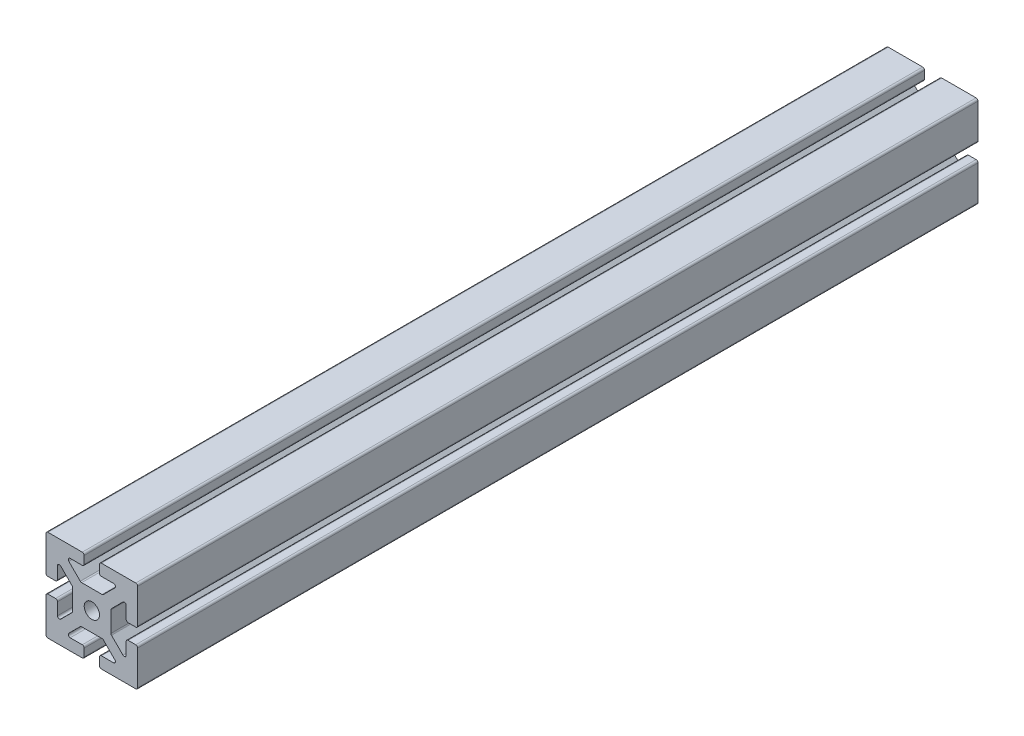
SolidWorks part; units mm, degrees
material "6061-T4 (SS)"
ref_plane "Front Plane" through (0, 0, 0) normal (0, 0, 1) x (1, 0, 0)
ref_plane "Top Plane" through (0, 0, 0) normal (0, 1, 0) x (1, 0, 0)
ref_plane "Right Plane" through (0, 0, 0) normal (1, 0, 0) x (0, 0, -1)
sketch "Sketch2" plane through (0, 0, 0) normal (0, 0, 1) x (1, 0, 0)
  line L0 (0, 0) -> (0, 2.5) construction
  line L1 (0, 0) -> (2.5, 0) construction
  line L2 (0, 2.5) -> (1.3358, 2.5)
  line L3 (1.5126, 2.5732) -> (3.0126, 4.0732)
  line L4 (2.8358, 4.5) -> (1.25, 4.5)
  line L5 (1, 4.75) -> (1, 5.75)
  line L6 (1.25, 6) -> (5.75, 6)
  line L7 (6, 5.75) -> (6, 1.25)
  line L8 (5.75, 1) -> (4.75, 1)
  line L9 (4.5, 1.25) -> (4.5, 2.8358)
  line L10 (4.0732, 3.0126) -> (2.5732, 1.5126)
  line L11 (2.5, 1.3358) -> (2.5, 0)
  line L12 (0, 0) -> (5.75, 5.75) construction
  line L13 (2.5, 0) -> (2.5, -1.3358)
  line L14 (2.5732, -1.5126) -> (4.0732, -3.0126)
  line L15 (4.5, -2.8358) -> (4.5, -1.25)
  line L16 (4.75, -1) -> (5.75, -1)
  line L17 (6, -1.25) -> (6, -5.75)
  line L18 (5.75, -6) -> (1.25, -6)
  line L19 (1, -5.75) -> (1, -4.75)
  line L20 (1.25, -4.5) -> (2.8358, -4.5)
  line L21 (3.0126, -4.0732) -> (1.5126, -2.5732)
  line L22 (1.3358, -2.5) -> (0, -2.5)
  line L23 (0, -2.5) -> (-1.3358, -2.5)
  line L24 (-1.5126, -2.5732) -> (-3.0126, -4.0732)
  line L25 (-2.8358, -4.5) -> (-1.25, -4.5)
  line L26 (-1, -4.75) -> (-1, -5.75)
  line L27 (-1.25, -6) -> (-5.75, -6)
  line L28 (-6, -5.75) -> (-6, -1.25)
  line L29 (-5.75, -1) -> (-4.75, -1)
  line L30 (-4.5, -1.25) -> (-4.5, -2.8358)
  line L31 (-4.0732, -3.0126) -> (-2.5732, -1.5126)
  line L32 (-2.5, -1.3358) -> (-2.5, 0)
  line L33 (-2.5, 0) -> (-2.5, 1.3358)
  line L34 (-2.5732, 1.5126) -> (-4.0732, 3.0126)
  line L35 (-4.5, 2.8358) -> (-4.5, 1.25)
  line L36 (-4.75, 1) -> (-5.75, 1)
  line L37 (-6, 1.25) -> (-6, 5.75)
  line L38 (-5.75, 6) -> (-1.25, 6)
  line L39 (-1, 5.75) -> (-1, 4.75)
  line L40 (-1.25, 4.5) -> (-2.8358, 4.5)
  line L41 (-3.0126, 4.0732) -> (-1.5126, 2.5732)
  line L42 (-1.3358, 2.5) -> (0, 2.5)
  circle A0 centre (0, 0) radius 1
  arc A1 (2.5732, 1.5126) -> (2.5, 1.3358) centre (2.75, 1.3358) ccw
  arc A2 (4.5, 2.8358) -> (4.0732, 3.0126) centre (4.25, 2.8358) ccw
  arc A3 (4.75, 1) -> (4.5, 1.25) centre (4.75, 1.25) cw
  arc A4 (6, 1.25) -> (5.75, 1) centre (5.75, 1.25) cw
  arc A5 (5.75, 6) -> (6, 5.75) centre (5.75, 5.75) cw
  arc A6 (1, 5.75) -> (1.25, 6) centre (1.25, 5.75) cw
  arc A7 (1.25, 4.5) -> (1, 4.75) centre (1.25, 4.75) cw
  arc A8 (3.0126, 4.0732) -> (2.8358, 4.5) centre (2.8358, 4.25) ccw
  arc A9 (1.3358, 2.5) -> (1.5126, 2.5732) centre (1.3358, 2.75) ccw
  arc A10 (1.5126, -2.5732) -> (1.3358, -2.5) centre (1.3358, -2.75) ccw
  arc A11 (2.8358, -4.5) -> (3.0126, -4.0732) centre (2.8358, -4.25) ccw
  arc A12 (1, -4.75) -> (1.25, -4.5) centre (1.25, -4.75) cw
  arc A13 (1.25, -6) -> (1, -5.75) centre (1.25, -5.75) cw
  arc A14 (6, -5.75) -> (5.75, -6) centre (5.75, -5.75) cw
  arc A15 (5.75, -1) -> (6, -1.25) centre (5.75, -1.25) cw
  arc A16 (4.5, -1.25) -> (4.75, -1) centre (4.75, -1.25) cw
  arc A17 (4.0732, -3.0126) -> (4.5, -2.8358) centre (4.25, -2.8358) ccw
  arc A18 (2.5, -1.3358) -> (2.5732, -1.5126) centre (2.75, -1.3358) ccw
  arc A19 (-2.5732, -1.5126) -> (-2.5, -1.3358) centre (-2.75, -1.3358) ccw
  arc A20 (-4.5, -2.8358) -> (-4.0732, -3.0126) centre (-4.25, -2.8358) ccw
  arc A21 (-4.75, -1) -> (-4.5, -1.25) centre (-4.75, -1.25) cw
  arc A22 (-6, -1.25) -> (-5.75, -1) centre (-5.75, -1.25) cw
  arc A23 (-5.75, -6) -> (-6, -5.75) centre (-5.75, -5.75) cw
  arc A24 (-1, -5.75) -> (-1.25, -6) centre (-1.25, -5.75) cw
  arc A25 (-1.25, -4.5) -> (-1, -4.75) centre (-1.25, -4.75) cw
  arc A26 (-3.0126, -4.0732) -> (-2.8358, -4.5) centre (-2.8358, -4.25) ccw
  arc A27 (-1.3358, -2.5) -> (-1.5126, -2.5732) centre (-1.3358, -2.75) ccw
  arc A28 (-1.5126, 2.5732) -> (-1.3358, 2.5) centre (-1.3358, 2.75) ccw
  arc A29 (-2.8358, 4.5) -> (-3.0126, 4.0732) centre (-2.8358, 4.25) ccw
  arc A30 (-1, 4.75) -> (-1.25, 4.5) centre (-1.25, 4.75) cw
  arc A31 (-1.25, 6) -> (-1, 5.75) centre (-1.25, 5.75) cw
  arc A32 (-6, 5.75) -> (-5.75, 6) centre (-5.75, 5.75) cw
  arc A33 (-5.75, 1) -> (-6, 1.25) centre (-5.75, 1.25) cw
  arc A34 (-4.5, 1.25) -> (-4.75, 1) centre (-4.75, 1.25) cw
  arc A35 (-4.0732, 3.0126) -> (-4.5, 2.8358) centre (-4.25, 2.8358) ccw
  arc A36 (-2.5, 1.3358) -> (-2.5732, 1.5126) centre (-2.75, 1.3358) ccw
  point P3 (0, 0)
  point P122 (0, 0)
  dimension "D1" = 2
  dimension "D7" = 0.25
  dimension "D3" = 2
  dimension "D4" = 2.5
  dimension "D5" = 2.5
  dimension "D6" = 2
  dimension "D8" = 1.5
  dimension "D9" = 1.5
  dimension "D2" = 4
extrude "Boss-Extrude1" add sketch "Sketch2" along normal mid plane 110 contours A36 L33 L32 A19 L31 A20 L30 A21 L29 A22 L28 A23 L27 A24 L26 A25 L25 A26 L24 A27 L23 L22 A10 L21 A11 L20 A12 L19 A13 L18 A14 L17 A15 L16 A16 L15 A17 L14 A18 L13 L11 A1 L10 A2 L9 A3 L8 A4 L7 A5 L6
equation "\"A\"= 1.5"
equation "\"B\"= 2"
equation "\"C\"= 110"
equation "\"D1@Sketch2\"=\"B\""
equation "\"D3@Sketch2\"=\"B\""
equation "\"D4@Sketch2\"=\"B\"/2+\"A\""
equation "\"D5@Sketch2\"=\"D4@Sketch2\""
equation "\"D6@Sketch2\"=\"B\""
equation "\"D8@Sketch2\"=\"A\""
equation "\"D9@Sketch2\"=\"A\""
equation "\"D1@Boss-Extrude1\"=\"C\""
